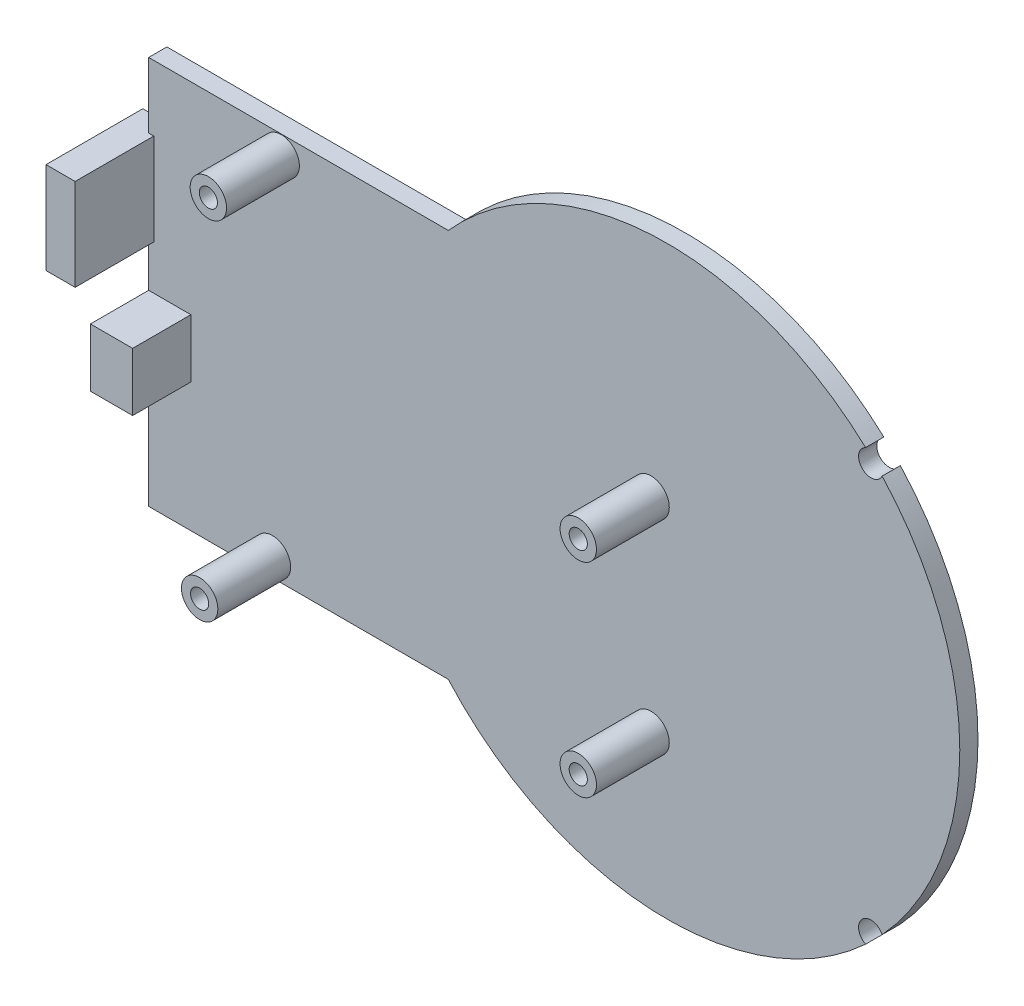
SolidWorks part; units mm, degrees
ref_plane "Front Plane" through (0, 0, 0) normal (0, 0, 1) x (1, 0, 0)
ref_plane "Top Plane" through (0, 0, 0) normal (0, 1, 0) x (1, 0, 0)
ref_plane "Right Plane" through (0, 0, 0) normal (1, 0, 0) x (0, 0, -1)
ref_plane "Plane1" through (0, 0, 6) normal (0, 0, 1) x (1, 0, 0)
sketch "Sketch2" plane through (0, 0, 6) normal (0, 0, 1) x (1, 0, 0)
  line L1 (-71.2, -26.7) -> (-20, -26.7)
  line L2 (-71.2, -26.7) -> (-71.2, 26.7)
  line L3 (-71.2, 26.7) -> (-20, 26.7)
  line L4 (-20, -26.7) -> (-20, 26.7)
extrude "Boss-Extrude2" add sketch "Sketch2" along normal blind 2.5
ref_plane "Plane2" through (0, 0, 8.5) normal (0, 0, 1) x (1, 0, 0)
sketch "Sketch3" plane through (0, 0, 6) normal (0, 0, 1) x (1, 0, 0)
  circle A0 centre (0, 0) radius 40.2
extrude "Boss-Extrude3" add sketch "Sketch3" along normal blind 2.5
sketch "Sketch4" plane through (0, 0, 8.5) normal (0, 0, 1) x (1, 0, 0)
  circle A0 centre (-54.2, -24.17) radius 2.5
  circle A1 centre (-53, 24.13) radius 2.5
  circle A2 centre (-2.2, -19.07) radius 2.5
  circle A3 centre (-2.2, 8.93) radius 2.5
extrude "Boss-Extrude4" add sketch "Sketch4" along normal blind 10
sketch "Sketch5" plane through (0, 0, 8.5) normal (0, 0, 1) x (1, 0, 0)
  line L1 (-71.2, -9) -> (-65.4, -9)
  line L2 (-71.2, -9) -> (-71.2, -1)
  line L3 (-71.2, -1) -> (-65.4, -1)
  line L4 (-65.4, -9) -> (-65.4, -1)
extrude "Boss-Extrude5" add sketch "Sketch5" along normal blind 8
sketch "Sketch6" plane through (0, 0, 6) normal (0, 0, 1) x (1, 0, 0)
  circle A0 centre (-54.2, -24.17) radius 1.25
  circle A1 centre (-53, 24.13) radius 1.25
  circle A2 centre (-2.2, -19.07) radius 1.25
  circle A3 centre (-2.2, 8.93) radius 1.25
  circle A4 centre (28, 28) radius 1.7
  circle A5 centre (28, -28) radius 1.7
extrude "Cut-Extrude1" cut sketch "Sketch6" along normal through all
ref_plane "Plane3" through (-71.2, 0, 0) normal (1, 0, 0) x (0, 0, -1)
sketch "Sketch7" plane through (-71.2, 0, 0) normal (1, 0, 0) x (0, 0, -1)
  circle A0 centre (-12.5, -5) radius 2.1
extrude "Cut-Extrude2" cut sketch "Sketch7" along normal blind 5.2
ref_plane "Plane4" through (0, 0, 6) normal (0, 0, 1) x (1, 0, 0)
sketch "Sketch8" plane through (0, 0, 6) normal (0, 0, 1) x (1, 0, 0)
  line L0 (-74.5, 5.1) -> (-70.5, 5.1)
  line L1 (-70.5, 5.1) -> (-70.5, 17.7)
  line L2 (-70.5, 17.7) -> (-74.5, 17.7)
  line L3 (-74.5, 17.7) -> (-74.5, 5.1)
extrude "Boss-Extrude6" add sketch "Sketch8" along normal blind 13.3
